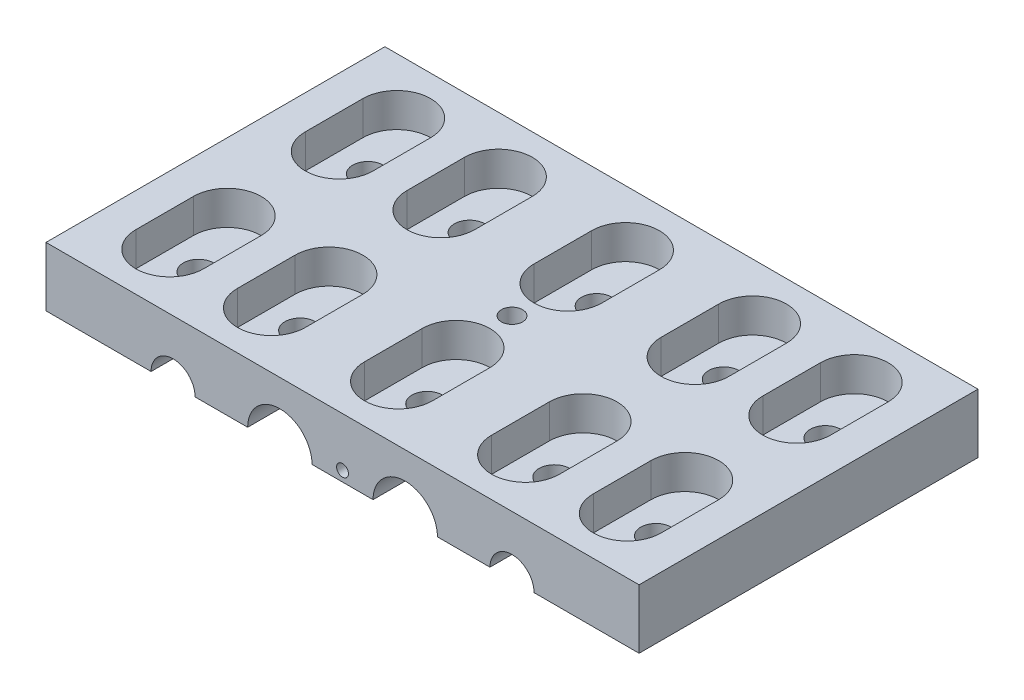
SolidWorks part; units mm, degrees
material "Copper"
ref_plane "Front Plane" through (0, 0, 0) normal (0, 0, 1) x (1, 0, 0)
ref_plane "Top Plane" through (0, 0, 0) normal (0, 1, 0) x (1, 0, 0)
ref_plane "Right Plane" through (0, 0, 0) normal (1, 0, 0) x (0, 0, -1)
sketch "Sketch1" plane through (0, 0, 0) normal (0, 1, 0) x (1, 0, 0)
  line L1 (-44.45, 25.4) -> (44.45, 25.4)
  line L2 (-44.45, 25.4) -> (-44.45, -25.4)
  line L3 (-44.45, -25.4) -> (44.45, -25.4)
  line L4 (44.45, 25.4) -> (44.45, -25.4)
  line L5 (-44.45, 25.4) -> (44.45, -25.4) construction
  line L6 (-44.45, -25.4) -> (44.45, 25.4) construction
  point P0 (0, 0)
  dimension "D1" = 88.9
  dimension "D2" = 50.8
extrude "Boss-Extrude1" add sketch "Sketch1" along normal blind 8.89
sketch "Sketch2" plane through (0, 8.89, 0) normal (0, 1, 0) x (1, 0, 0)
  line L0 (-34.29, 17.018) -> (-34.29, 8.382) construction
  line L1 (-29.21, 17.018) -> (-29.21, 8.382)
  line L2 (-39.37, 17.018) -> (-39.37, 8.382)
  line L3 (-44.45, 25.4) -> (-44.45, -25.4) construction
  line L4 (44.45, 25.4) -> (-44.45, 25.4) construction
  line L5 (-19.05, 17.018) -> (-19.05, 8.382) construction
  line L6 (-13.97, 17.018) -> (-13.97, 8.382)
  line L7 (-24.13, 17.018) -> (-24.13, 8.382)
  line L8 (0, 17.018) -> (0, 8.382) construction
  line L9 (5.08, 17.018) -> (5.08, 8.382)
  line L10 (-5.08, 17.018) -> (-5.08, 8.382)
  line L11 (19.05, 17.018) -> (19.05, 8.382) construction
  line L12 (24.13, 17.018) -> (24.13, 8.382)
  line L13 (13.97, 17.018) -> (13.97, 8.382)
  line L14 (34.29, 17.018) -> (34.29, 8.382) construction
  line L15 (39.37, 17.018) -> (39.37, 8.382)
  line L16 (29.21, 17.018) -> (29.21, 8.382)
  arc A0 (-29.21, 17.018) -> (-39.37, 17.018) centre (-34.29, 17.018) ccw
  arc A1 (-39.37, 8.382) -> (-29.21, 8.382) centre (-34.29, 8.382) ccw
  arc A2 (-13.97, 17.018) -> (-24.13, 17.018) centre (-19.05, 17.018) ccw
  arc A3 (-24.13, 8.382) -> (-13.97, 8.382) centre (-19.05, 8.382) ccw
  arc A4 (5.08, 17.018) -> (-5.08, 17.018) centre (0, 17.018) ccw
  arc A5 (-5.08, 8.382) -> (5.08, 8.382) centre (0, 8.382) ccw
  arc A6 (24.13, 17.018) -> (13.97, 17.018) centre (19.05, 17.018) ccw
  arc A7 (13.97, 8.382) -> (24.13, 8.382) centre (19.05, 8.382) ccw
  arc A8 (39.37, 17.018) -> (29.21, 17.018) centre (34.29, 17.018) ccw
  arc A9 (29.21, 8.382) -> (39.37, 8.382) centre (34.29, 8.382) ccw
  circle A10 centre (-34.29, 12.7) radius 2.286
  circle A11 centre (-19.05, 12.7) radius 2.286
  circle A12 centre (0, 12.7) radius 2.286
  circle A13 centre (19.05, 12.7) radius 2.286
  circle A14 centre (34.29, 12.7) radius 2.286
  point P2 (-34.29, 12.7)
  point P15 (-19.05, 12.7)
  point P21 (0, 12.7)
  point P28 (19.05, 12.7)
  point P36 (34.29, 12.7)
  dimension "D1" = 5.08
  dimension "D13" = 8.382
  dimension "D14" = 8.382
  dimension "D16" = 8.382
  dimension "D17" = 4.572
  dimension "D18" = 4.572
  dimension "D19" = 4.572
  dimension "D20" = 4.572
  dimension "D21" = 4.572
  dimension "D22" = 5.08
  dimension "D3" = 8.636
  dimension "D4" = 8.382
  dimension "D9" = 5.08
  dimension "D10" = 8.89
  dimension "D11" = 8.89
  dimension "D12" = 5.08
  dimension "D15" = 8.382
  dimension "D5" = 2
  dimension "D6" = 2
  dimension "D7" = 2
  dimension "D8" = 2
sketch "Sketch3" plane through (0, 0, 25.4) normal (0, 0, 1) x (1, 0, 0)
  line L0 (-44.45, 0) -> (44.45, 0) construction
  line L1 (44.45, 8.89) -> (44.45, 0) construction
  circle A0 centre (6.35, 1.524) radius 0.889
  dimension "D1" = 1.778
  dimension "D3" = 38.1
  dimension "D2" = 1.524
extrude "Cut-Extrude3" cut sketch "Sketch3" against normal blind 9.652
sketch "Sketch4" plane through (0, 0, 25.4) normal (0, 0, 1) x (1, 0, 0)
  line L0 (-44.45, 0) -> (44.45, 0) construction
  line L1 (4.572, 0) -> (14.224, 0)
  arc A0 (14.224, 0) -> (4.572, 0) centre (9.398, 0) ccw
  point P1 (0, 0)
  dimension "D1" = 4.826
  dimension "D2" = 4.572
extrude "Cut-Extrude4" cut sketch "Sketch4" against normal through all
sketch "Sketch5" plane through (0, 0, 25.4) normal (0, 0, 1) x (1, 0, 0)
  line L0 (14.224, 0) -> (44.45, 0) construction
  line L1 (22.098, 0) -> (28.702, 0)
  arc A0 (28.702, 0) -> (22.098, 0) centre (25.4, 0) ccw
  dimension "D1" = 3.302
  dimension "D2" = 7.874
extrude "Cut-Extrude5" cut sketch "Sketch5" against normal through all
sketch "Sketch6" plane through (0, 0, 25.4) normal (0, 0, 1) x (1, 0, 0)
  line L0 (-44.45, 0) -> (4.572, 0) construction
  line L1 (-28.702, 0) -> (-22.098, 0)
  line L2 (-14.224, 0) -> (-4.572, 0)
  arc A0 (-4.572, 0) -> (-14.224, 0) centre (-9.398, 0) ccw
  arc A1 (-22.098, 0) -> (-28.702, 0) centre (-25.4, 0) ccw
  dimension "D1" = 3.302
  dimension "D2" = 4.826
  dimension "D3" = 7.874
  dimension "D4" = 9.144
extrude "Cut-Extrude6" cut sketch "Sketch6" against normal through all
extrude "Cut-Extrude8" cut sketch "Sketch2" against normal blind 5.08
sketch "Sketch11" plane through (0, 8.89, 0) normal (0, 1, 0) x (1, 0, 0)
  circle A0 centre (-34.29, 12.7) radius 2.286
  circle A1 centre (-19.05, 12.7) radius 2.286
  circle A2 centre (0, 12.7) radius 2.286
  circle A3 centre (19.05, 12.7) radius 2.286
  circle A4 centre (34.29, 12.7) radius 2.286
extrude "Cut-Extrude9" cut sketch "Sketch11" against normal through all
pattern_linear "LPattern5" count 2 spacing 25.4 along (0, 0, 1) of "Cut-Extrude8"
pattern_linear "LPattern7" count 2 spacing 25.4 along (0, 0, 1) of "Cut-Extrude9"
sketch "Sketch12" plane through (0, 8.89, 0) normal (0, 1, 0) x (1, 0, 0)
  circle A0 centre (0, 0) radius 1.5875
  dimension "D1" = 3.175
extrude "Cut-Extrude10" cut sketch "Sketch12" against normal through all
sketch "Sketch13" plane through (0, 0, 25.4) normal (0, 0, 1) x (1, 0, 0)
  line L0 (-4.572, 0) -> (4.572, 0) construction
  circle A0 centre (0, 1.524) radius 0.889
  arc A2 (-4.572, 0) -> (-14.224, 0) centre (-9.398, 0) ccw construction
  dimension "D2" = 1.778
  dimension "D3" = 9.398
  dimension "D1" = 1.524
extrude "Cut-Extrude11" cut sketch "Sketch13" against normal blind 9.652
